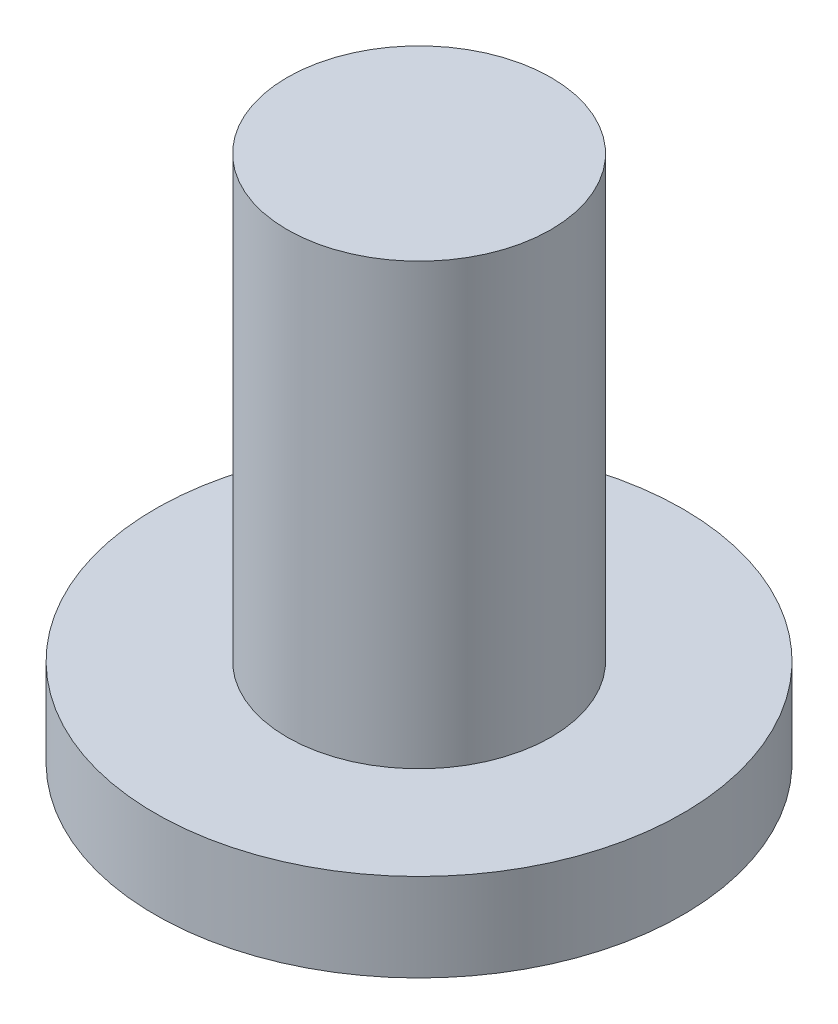
SolidWorks part; units mm, degrees
ref_plane "Front Plane" through (0, 0, 0) normal (0, 0, 1) x (1, 0, 0)
ref_plane "Top Plane" through (0, 0, 0) normal (0, 1, 0) x (1, 0, 0)
ref_plane "Right Plane" through (0, 0, 0) normal (1, 0, 0) x (0, 0, -1)
sketch "Sketch1" plane through (0, 0, 0) normal (0, 0, 1) x (1, 0, 0)
  line L0 (0, 0) -> (0, 12)
  line L1 (0, 12) -> (3, 12)
  line L2 (3, 12) -> (3, 2)
  line L3 (3, 2) -> (6, 2)
  line L4 (6, 2) -> (6, 0)
  line L5 (6, 0) -> (0, 0)
  dimension "D1" = 6
  dimension "D2" = 3
  dimension "D3" = 2
  dimension "D4" = 12
revolve "Revolve1" add sketch "Sketch1" angle 360 about L0
